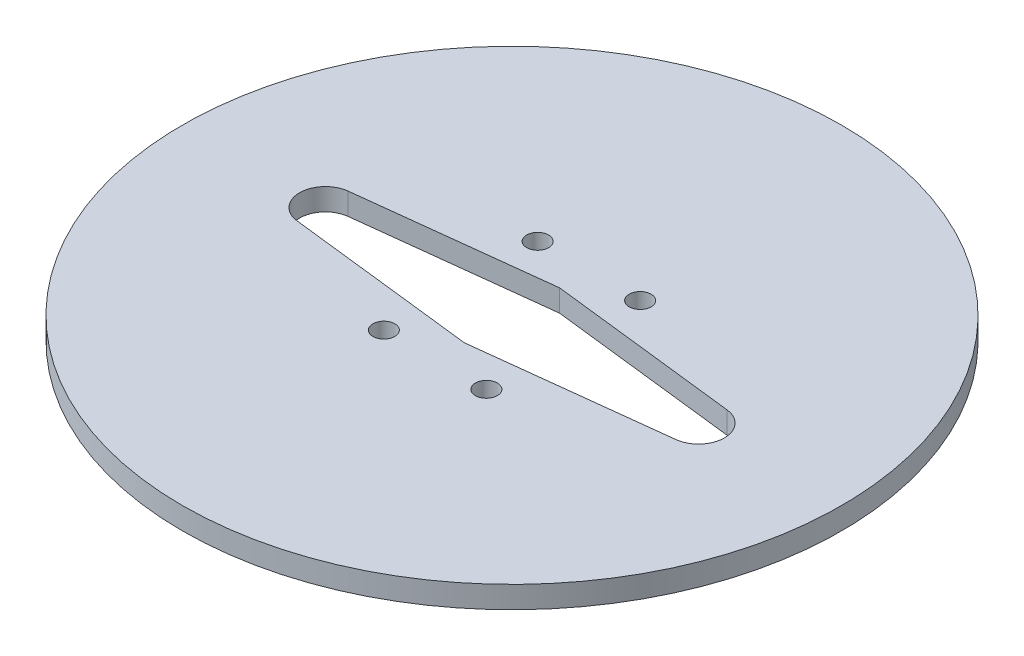
SolidWorks part; units mm, degrees
ref_plane "Front Plane" through (0, 0, 0) normal (0, 0, 1) x (1, 0, 0)
ref_plane "Top Plane" through (0, 0, 0) normal (0, 1, 0) x (1, 0, 0)
ref_plane "Right Plane" through (0, 0, 0) normal (1, 0, 0) x (0, 0, -1)
sketch "Sketch1" plane through (0, 0, 0) normal (0, 1, 0) x (1, 0, 0)
  circle A0 centre (0, 0) radius 45
  dimension "D1" = 90
extrude "Boss-Extrude1" add sketch "Sketch1" along normal blind 3 contours A0
sketch "Sketch3" plane through (0, 3, 0) normal (0, 1, 0) x (1, 0, 0)
  line L0 (-25.8823, 3.5) -> (0, 6.5)
  line L1 (0, 6.5) -> (25.8823, 3.5)
  line L2 (25.8823, -3.5) -> (0, -6.5)
  line L3 (0, -6.5) -> (-25.8823, -3.5)
  arc A0 (-25.8823, 3.5) -> (-25.8823, -3.5) centre (-25.4766, 0) ccw
  arc A1 (25.8823, -3.5) -> (25.8823, 3.5) centre (25.4766, 0) ccw
  point P7 (0, -6.25)
  point P8 (-29, 0)
  point P9 (29, 0)
  point P10 (0, 6.25)
  point P12 (0, 0)
  point P13 (0, 0)
  dimension "D1" = 58
  dimension "D2" = 13
  dimension "D3" = 7
  dimension "D4" = 6.5
  dimension "D5" = 29
extrude "Cut-Extrude1" cut sketch "Sketch3" against normal blind 3
sketch "Sketch4" plane through (0, 3, 0) normal (0, 1, 0) x (1, 0, 0)
  circle A0 centre (-7, -10.5) radius 1.5
  circle A1 centre (7, -10.5) radius 1.5
  circle A2 centre (-7, 10.5) radius 1.5
  circle A3 centre (7, 10.5) radius 1.5
  point P0 (0, 0)
  dimension "D17" = 7
  dimension "D2" = 3
  dimension "D3" = 3
  dimension "D4" = 3
  dimension "D5" = 3
  dimension "D6" = 4
  dimension "D7" = 4
  dimension "D15" = 7
  dimension "D16" = 7
  dimension "D18" = 7
extrude "Cut-Extrude2" cut sketch "Sketch4" against normal blind 3
